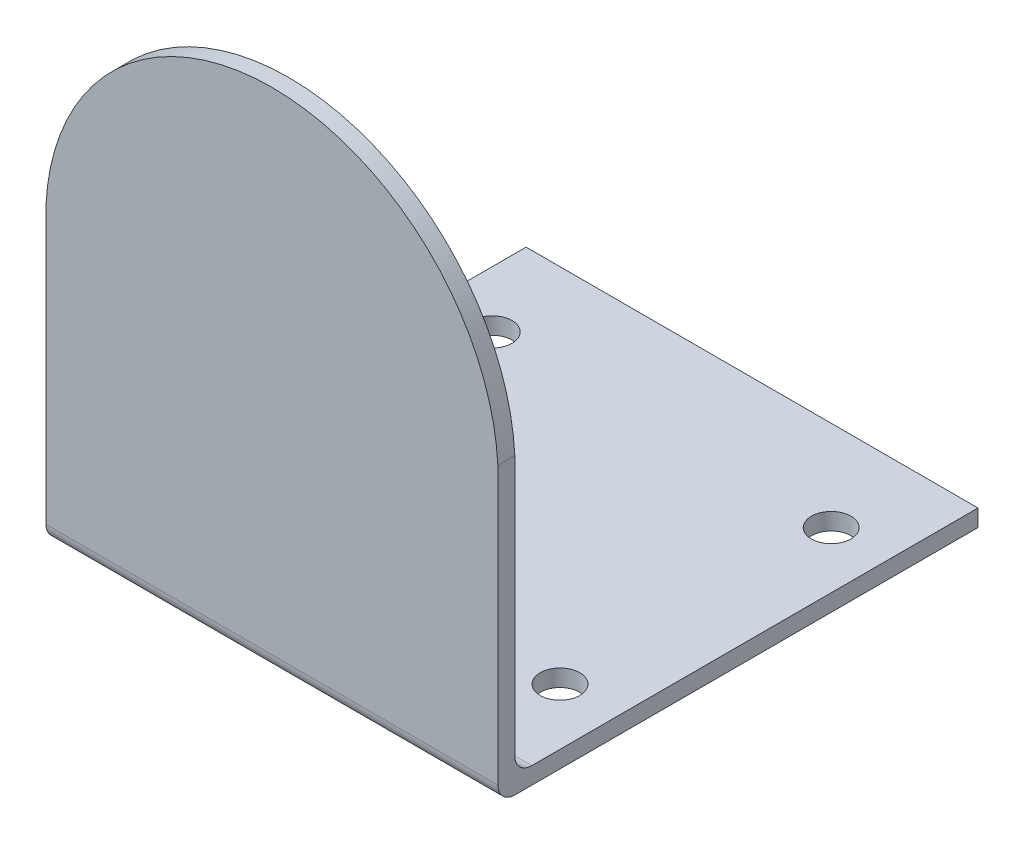
SolidWorks part; units mm, degrees
ref_plane "前视基准面" through (0, 0, 0) normal (0, 0, 1) x (1, 0, 0)
ref_plane "上视基准面" through (0, 0, 0) normal (0, 1, 0) x (1, 0, 0)
ref_plane "右视基准面" through (0, 0, 0) normal (1, 0, 0) x (0, 0, -1)
sketch "草图1" plane through (0, 0, 0) normal (0, 1, 0) x (1, 0, 0)
  line L0 (-1.4096, 20.7121) -> (-1.4096, -28.537) construction
  line L1 (-21.4096, 17.4113) -> (18.5904, 17.4113)
  line L2 (-21.4096, 17.4113) -> (-21.4096, -23.5887)
  line L3 (-21.4096, -23.5887) -> (18.5904, -23.5887)
  line L4 (18.5904, 17.4113) -> (18.5904, -23.5887)
  line L5 (-24.3753, -2.5887) -> (21.208, -2.5887) construction
  circle A0 centre (-16.4096, 9.4113) radius 1.75
  circle A1 centre (-16.4096, -14.5887) radius 1.75
  circle A2 centre (13.5904, 9.4113) radius 1.75
  circle A3 centre (13.5904, -14.5887) radius 1.75
  dimension "D3" = 24
  dimension "D5" = 8
  dimension "D1" = 41
  dimension "D2" = 40
  dimension "D4" = 30
extrude "凸台-拉伸1" add sketch "草图1" along normal blind 1.5
sketch "草图2" plane through (0, 0, 23.5887) normal (0, 0, 1) x (1, 0, 0)
  line L0 (-21.4096, 1.5) -> (-21.4096, 26.0233)
  line L2 (-21.4096, 1.5) -> (-21.4096, 0)
  line L3 (-21.4096, 0) -> (18.5904, 0)
  line L4 (18.5904, 1.5) -> (18.5904, 0)
  line L5 (18.5904, 1.5) -> (18.5904, 26.0233)
  arc A0 (-21.4096, 26.0233) -> (18.5904, 26.0233) centre (-1.4096, 24.9724) cw
  point P10 (-1.4096, 45)
  dimension "D1" = 45
extrude "凸台-拉伸2" add sketch "草图2" along normal blind 1.5
fillet "圆角1" radius 1.5 2 edges at (-1.4096, 0, 25.0887) (-1.4096, 1.5, 23.5887)
